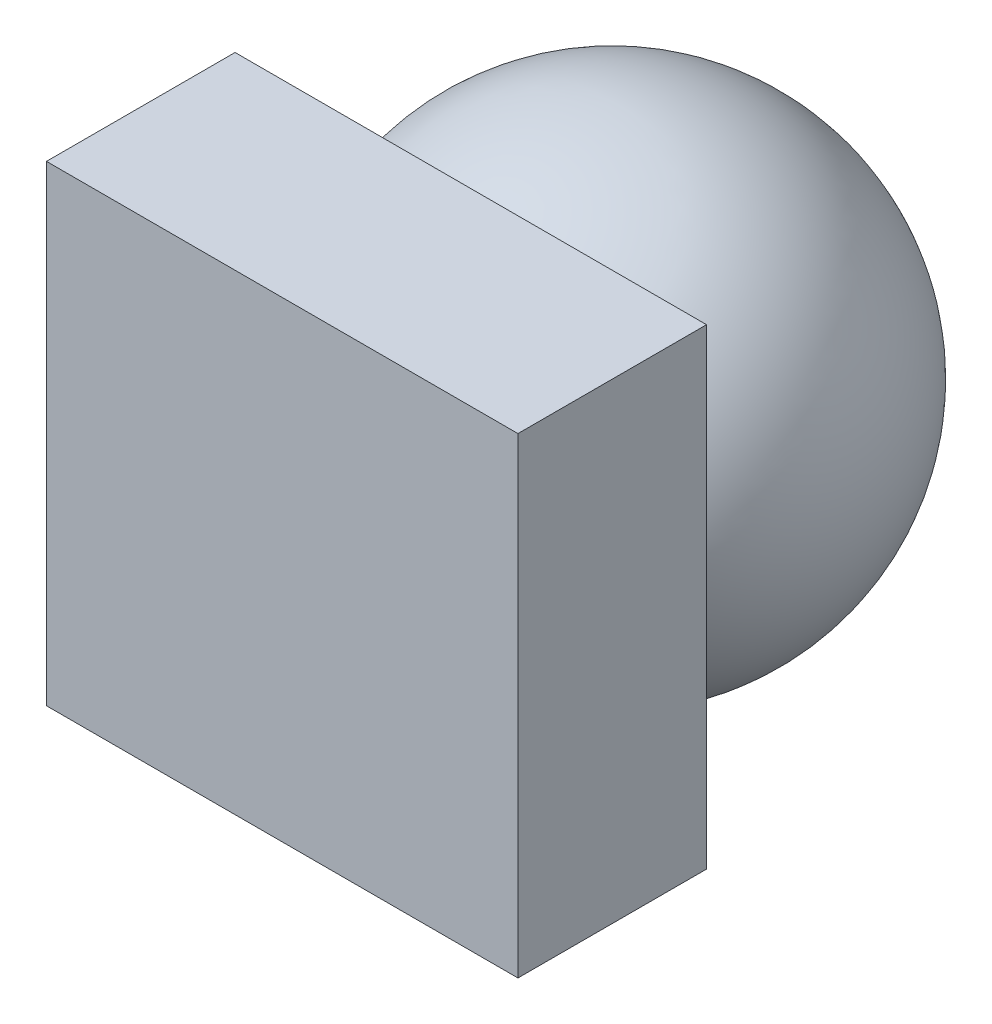
SolidWorks part; units mm, degrees
ref_plane "Front Plane" through (0, 0, 0) normal (0, 0, 1) x (1, 0, 0)
ref_plane "Top Plane" through (0, 0, 0) normal (0, 1, 0) x (1, 0, 0)
ref_plane "Right Plane" through (0, 0, 0) normal (1, 0, 0) x (0, 0, -1)
sketch "Sketch1" plane through (0, 0, 0) normal (0, 0, 1) x (1, 0, 0)
  line L1 (0, 0) -> (25, 0)
  line L2 (0, 0) -> (0, 25)
  line L3 (0, 25) -> (25, 25)
  line L4 (25, 0) -> (25, 25)
  dimension "D1" = 25
  dimension "D2" = 25
extrude "Boss-Extrude1" add sketch "Sketch1" along normal blind 10
ref_plane "Plane1" through (0, 12.5, 0) normal (0, -1, 0) x (-1, 0, 0)
sketch "Sketch3" plane through (0, 12.5, 0) normal (0, -1, 0) x (-1, 0, 0)
  line L0 (-12.5, 20) -> (-12.5, -5)
  line L2 (-12.5, 0) -> (-12.5, -10) construction
  line L3 (0, 0) -> (-25, 0) construction
  line L4 (0, -10) -> (-25, -10) construction
  arc A0 (-12.5, -5) -> (-12.5, 20) centre (-12.5, 7.5) ccw
  point P1 (-12.5, -4.5707)
  dimension "D1" = 12.5
revolve "Revolve1" add sketch "Sketch3" angle 360 about L2
